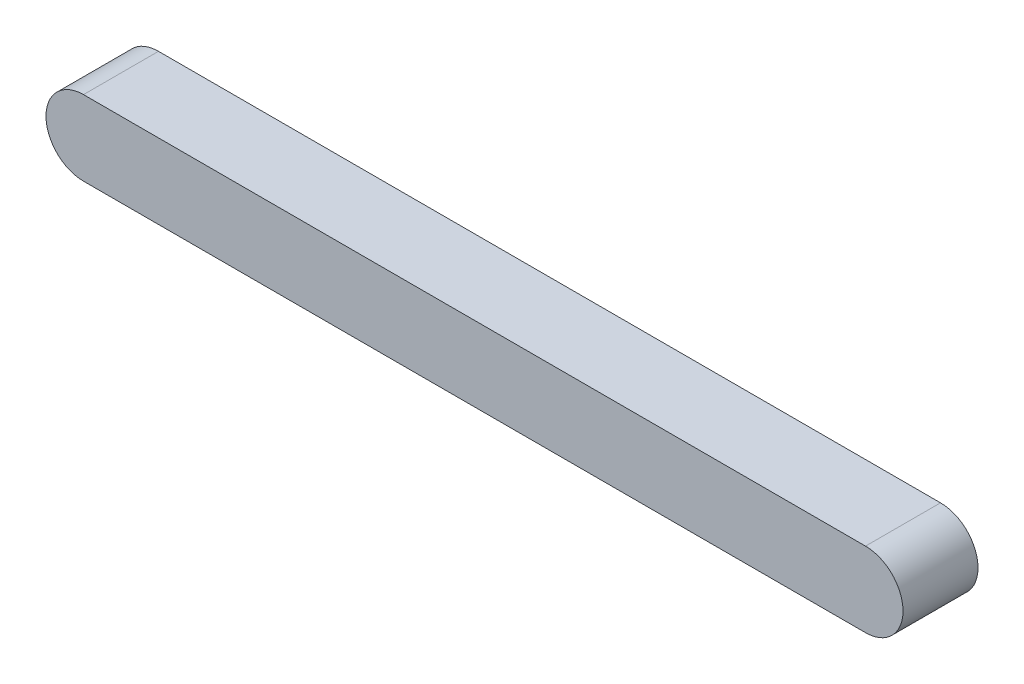
SolidWorks part; units mm, degrees
ref_plane "Ön Düzlem" through (0, 0, 0) normal (0, 0, 1) x (1, 0, 0)
ref_plane "Üst Düzlem" through (0, 0, 0) normal (0, 1, 0) x (1, 0, 0)
ref_plane "Sağ Düzlem" through (0, 0, 0) normal (1, 0, 0) x (0, 0, -1)
sketch "Çizim1" plane through (0, 0, 0) normal (0, 0, 1) x (1, 0, 0)
  line L0 (-36.5, 0) -> (36.5, 0) construction
  line L1 (-36.5, 3.5) -> (36.5, 3.5)
  line L2 (-36.5, -3.5) -> (36.5, -3.5)
  arc A0 (-36.5, 3.5) -> (-36.5, -3.5) centre (-36.5, 0) ccw
  arc A1 (36.5, -3.5) -> (36.5, 3.5) centre (36.5, 0) ccw
  point P3 (0, 0)
  point P8 (-40, 0)
  dimension "D1" = 3.5
  dimension "D2" = 73
  dimension "D3" = 76.5
extrude "Yükseklik-Ekstrüzyon1" add sketch "Çizim1" along normal blind 7
